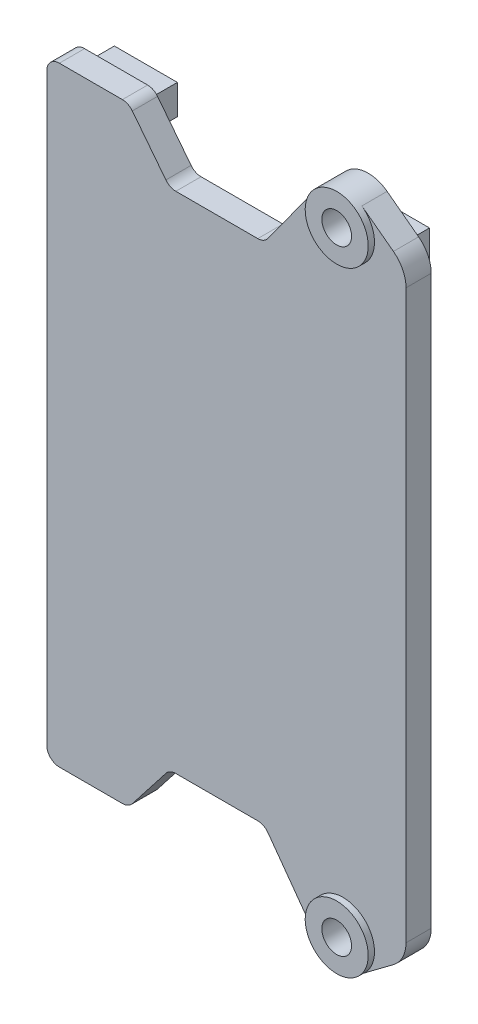
SolidWorks part; units mm, degrees
ref_plane "Front Plane" through (0, 0, 0) normal (0, 0, 1) x (1, 0, 0)
ref_plane "Top Plane" through (0, 0, 0) normal (0, 1, 0) x (1, 0, 0)
ref_plane "Right Plane" through (0, 0, 0) normal (1, 0, 0) x (0, 0, -1)
sketch "Sketch1" plane through (0, 0, 0) normal (0, 0, 1) x (1, 0, 0)
  line L0 (0, 0) -> (190.5, 0) construction
  line L1 (190.5, 28.575) -> (190.5, -28.575) construction
  line L2 (-190.5, -28.575) -> (-190.5, 28.575) construction
  line L3 (190.5, -25.4) -> (-190.5, -25.4) construction
  line L4 (190.5, -25.4) -> (190.5, 25.4) construction
  line L5 (190.5, 25.4) -> (-190.5, 25.4) construction
  line L6 (-190.5, -25.4) -> (-190.5, 25.4) construction
  line L7 (190.5, -25.4) -> (-190.5, 25.4) construction
  line L8 (190.5, 25.4) -> (-190.5, -25.4) construction
  dimension "D1" = 50.8
sketch "Sketch2" plane through (0, 0, 0) normal (0, 0, 1) x (1, 0, 0)
  line L0 (190.5, 25.4) -> (-190.5, 25.4) construction
  line L1 (190.5, 28.575) -> (190.5, -28.575) construction
  line L2 (186.055, 33.4962) -> (189.23, 31.115)
  line L3 (190.5, 28.575) -> (190.5, 0)
  line L4 (190.5, 0) -> (154.305, 0)
  line L5 (0, 0) -> (190.5, 0) construction
  line L6 (154.305, 0) -> (154.305, 29.44)
  line L7 (155.575, 30.71) -> (161.925, 30.71)
  line L8 (162.9263, 30.2212) -> (166.3062, 25.8888)
  line L9 (167.3075, 25.4) -> (175.5637, 25.4)
  line L10 (176.5927, 25.9257) -> (181.5774, 32.817)
  line L13 (161.925, 29.44) -> (155.575, 29.44) construction
  line L14 (161.925, 29.44) -> (161.925, 26.44) construction
  line L15 (161.925, 26.44) -> (155.575, 26.44) construction
  line L16 (155.575, 29.44) -> (155.575, 26.44) construction
  line L17 (161.925, 29.44) -> (155.575, 26.44) construction
  line L18 (161.925, 26.44) -> (155.575, 29.44) construction
  circle A0 centre (184.15, 30.9562) radius 5.5563 construction
  circle A1 centre (184.15, 30.9562) radius 1.5
  circle A2 centre (184.15, 30.9562) radius 4.5 construction
  arc A4 (186.055, 33.4962) -> (181.5774, 32.817) centre (184.15, 30.9562) ccw
  arc A5 (189.23, 31.115) -> (190.5, 28.575) centre (187.325, 28.575) cw
  arc A6 (190.5, 28.575) -> (187.325, 31.75) centre (187.325, 28.575) ccw construction
  arc A7 (190.5, 28.575) -> (187.325, 31.75) centre (187.325, 28.575) ccw construction
  arc A8 (176.5927, 25.9257) -> (175.5637, 25.4) centre (175.5637, 26.67) cw
  arc A9 (167.3075, 25.4) -> (166.3062, 25.8888) centre (167.3075, 26.67) cw
  arc A10 (162.9263, 30.2212) -> (161.925, 30.71) centre (161.925, 29.44) ccw
  arc A11 (155.575, 30.71) -> (154.305, 29.44) centre (155.575, 29.44) ccw
  point P21 (162.3696, 29.44)
  point P27 (158.75, 27.94)
  point P32 (176.2125, 25.4)
  point P36 (166.6875, 25.4)
  point P41 (155.5016, 29.44)
  dimension "D1" = 3
  dimension "D2" = 11.1125
  dimension "D3" = 9
  dimension "D5" = 6.35
  dimension "D8" = 1.27
  dimension "D4" = 6.35
  dimension "D6" = 14.2875
  dimension "D7" = 9.525
  dimension "D9" = 31.75
  dimension "D10" = 6.35
  dimension "D11" = 3
  dimension "D12" = 2.54
extrude "Boss-Extrude1" add sketch "Sketch2" along normal blind 2.54 contours L7 A11 L6 L4 L3 A5 L2 A4 L10 A8 L9 A9 L8 A10
sketch "Sketch3" plane through (0, 0, 2.54) normal (0, 0, 1) x (1, 0, 0)
  circle A0 centre (184.15, 30.9562) radius 1.5
  circle A1 centre (184.15, 30.9562) radius 3.175
extrude "Boss-Extrude2" add sketch "Sketch3" along normal offset from surface (0.635 mm away) 3.175 up to face at (185.65, 30.9562, 0)
sketch "Sketch4" plane through (0, 0, 0) normal (0, 0, -1) x (-1, 0, 0)
  line L0 (0, 0) -> (-190.5, 0) construction
  line L1 (-187.325, 29.44) -> (-180.975, 29.44)
  line L2 (-187.325, 29.44) -> (-187.325, 26.44)
  line L3 (-187.325, 26.44) -> (-180.975, 26.44)
  line L4 (-180.975, 29.44) -> (-180.975, 26.44)
  line L5 (-187.325, 29.44) -> (-180.975, 26.44) construction
  line L6 (-187.325, 26.44) -> (-180.975, 29.44) construction
  line L7 (-161.925, 29.44) -> (-155.575, 29.44)
  line L8 (-161.925, 29.44) -> (-161.925, 26.44)
  line L9 (-161.925, 26.44) -> (-155.575, 26.44)
  line L10 (-155.575, 29.44) -> (-155.575, 26.44)
  line L11 (-161.925, 29.44) -> (-155.575, 26.44) construction
  line L12 (-161.925, 26.44) -> (-155.575, 29.44) construction
  line L13 (-190.5, -25.4) -> (-190.5, 25.4) construction
  point P0 (-184.15, 27.94)
  point P5 (-158.75, 27.94)
  point P12 (0, 0)
  dimension "D1" = 27.94
  dimension "D2" = 6.35
  dimension "D3" = 3
  dimension "D4" = 6.35
  dimension "D5" = 25.4
extrude "Boss-Extrude3" add sketch "Sketch4" along normal blind 3
mirror "Mirror1" about plane through (0, 0, 0) normal (0, 1, 0) of bodies 104 102
